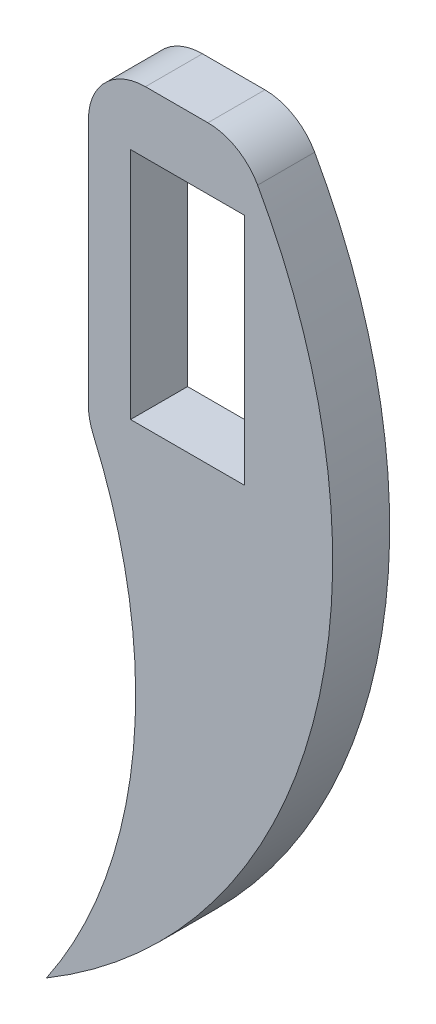
SolidWorks part; units mm, degrees
ref_plane "Plan de face" through (0, 0, 0) normal (0, 0, 1) x (1, 0, 0)
ref_plane "Plan de dessus" through (0, 0, 0) normal (0, 1, 0) x (1, 0, 0)
ref_plane "Plan de droite" through (0, 0, 0) normal (1, 0, 0) x (0, 0, -1)
sketch "Esquisse1" plane through (0, 0, 0) normal (0, 0, 1) x (1, 0, 0)
  line L0 (-7.3919, 10.8503) -> (19.2239, 10.8503)
  line L1 (0, 0) -> (20, 0)
  line L2 (0, 0) -> (0, -41)
  line L3 (0, -41) -> (20, -41)
  line L4 (20, 0) -> (20, -41)
  line L5 (-7.3919, 10.8503) -> (-7.3919, -44.6741)
  arc A0 (19.2239, 10.8503) -> (-14.7578, -133.1954) centre (-67.7024, -44.6741) cw
  arc A1 (-14.7578, -133.1954) -> (-7.3919, -44.6741) centre (-89.2649, -82.4286) ccw
  dimension "D1" = 20
extrude "Boss.-Extru.1" add sketch "Esquisse1" along normal blind 10
fillet "Congé1" radius 10 1 edges at (19.2239, 10.8503, 5)
fillet "Congé2" radius 10 2 edges at (-7.3919, -44.6741, 5) (-7.3919, 10.8503, 5)
